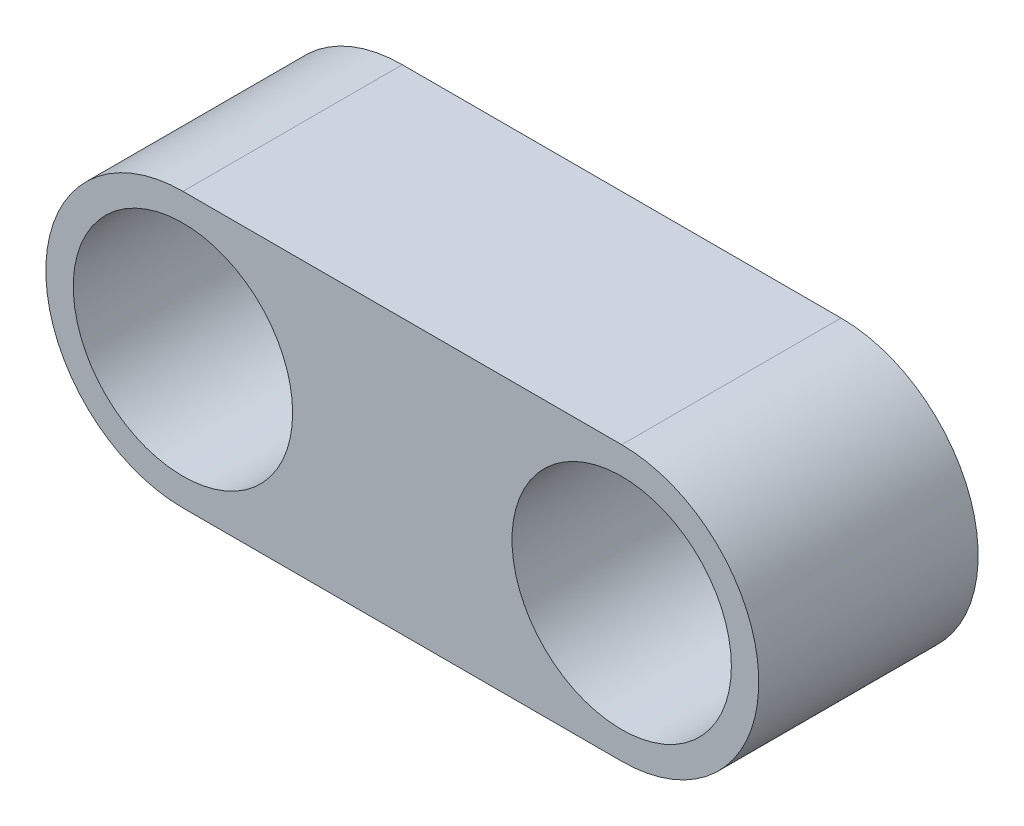
SolidWorks part; units mm, degrees
material "PVC Rigid"
ref_plane "Front Plane" through (0, 0, 0) normal (0, 0, 1) x (1, 0, 0)
ref_plane "Top Plane" through (0, 0, 0) normal (0, 1, 0) x (1, 0, 0)
ref_plane "Right Plane" through (0, 0, 0) normal (1, 0, 0) x (0, 0, -1)
sketch "Sketch1" plane through (0, 0, 0) normal (0, 0, 1) x (1, 0, 0)
  line L0 (-100.6358, 0) -> (0.9642, 0) construction
  line L1 (-100.6358, 0) -> (0.9642, 0) construction
  line L2 (-100.6358, 31.75) -> (0.9642, 31.75)
  line L3 (-100.6358, -31.75) -> (0.9642, -31.75)
  arc A0 (-100.6358, 31.75) -> (-100.6358, -31.75) centre (-100.6358, 0) ccw
  arc A1 (0.9642, -31.75) -> (0.9642, 31.75) centre (0.9642, 0) ccw
  circle A2 centre (-100.6358, 0) radius 25.4
  circle A3 centre (0.9642, 0) radius 25.4
  point P3 (-49.8358, 0)
  dimension "D3" = 50.8
  dimension "D1" = 63.5
  dimension "D2" = 101.6
extrude "Boss-Extrude1" add sketch "Sketch1" along normal blind 50.8
